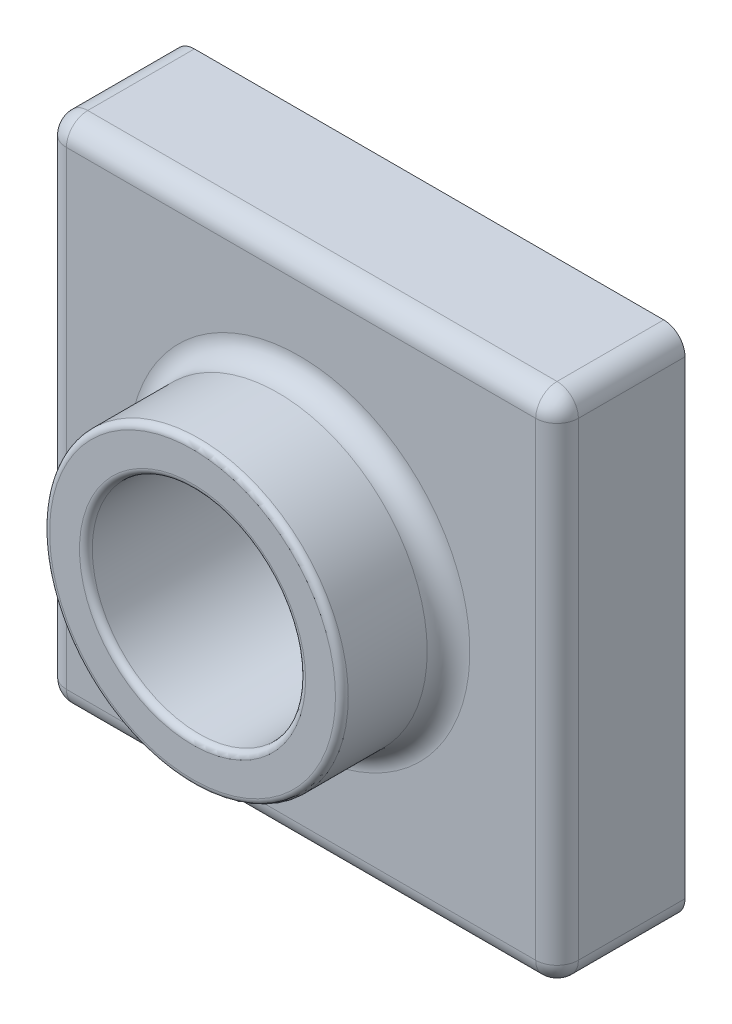
SolidWorks part; units mm, degrees
ref_plane "Front Plane" through (0, 0, 0) normal (0, 0, 1) x (1, 0, 0)
ref_plane "Top Plane" through (0, 0, 0) normal (0, 1, 0) x (1, 0, 0)
ref_plane "Right Plane" through (0, 0, 0) normal (1, 0, 0) x (0, 0, -1)
sketch "Sketch1" plane through (0, 0, 0) normal (0, 0, 1) x (1, 0, 0)
  line L1 (0, 0) -> (120, 0)
  line L2 (0, 0) -> (0, 120)
  line L3 (0, 120) -> (120, 120)
  line L4 (120, 0) -> (120, 120)
  dimension "D1" = 120
  dimension "D2" = 120
extrude "Boss-Extrude1" add sketch "Sketch1" along normal blind 30
sketch "Sketch3" plane through (0, 0, 30) normal (0, 0, 1) x (1, 0, 0)
  line L0 (120, 120) -> (0, 120) construction
  line L1 (0, 120) -> (0, 0) construction
  circle A0 centre (59.5646, 60) radius 35
  dimension "D1" = 70
  dimension "D2" = 60
  dimension "D3" = 59.5646
extrude "Boss-Extrude4" add sketch "Sketch3" along normal blind 25 contours A0
sketch "Sketch7" plane through (0, 0, 0) normal (0, 0, -1) x (-1, 0, 0)
  circle A0 centre (-59.5646, 60) radius 25
  dimension "D1" = 50
extrude "Cut-Extrude1" cut sketch "Sketch7" against normal through all
fillet "Fillet1" radius 5 9 edges at (60, 120, 30) (120, 60, 30) (60, 0, 30) (0, 60, 30) (94.5646, 60, 30) (0, 0, 15) (120, 0, 15) (0, 120, 15) (120, 120, 15)
fillet "Fillet2" radius 1.5 2 edges at (94.5646, 60, 55) (34.5646, 60, 55)
shell "Shell1" thickness 2
